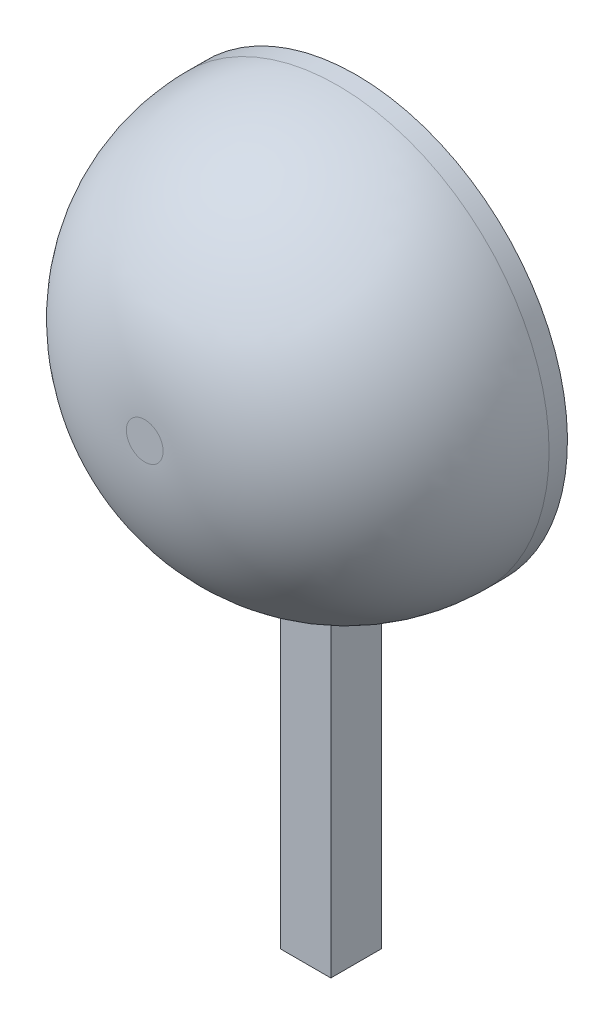
SolidWorks part; units mm, degrees
ref_plane "Front Plane" through (0, 0, 0) normal (0, 0, 1) x (1, 0, 0)
ref_plane "Top Plane" through (0, 0, 0) normal (0, 1, 0) x (1, 0, 0)
ref_plane "Right Plane" through (0, 0, 0) normal (1, 0, 0) x (0, 0, -1)
sketch "Sketch2" plane through (0, 0, 0) normal (0, 0, 1) x (1, 0, 0)
  line L0 (-24.3651, 0) -> (30.0337, 0)
  circle A0 centre (0, 23) radius 23
  dimension "D1" = 46
extrude "Boss-Extrude1" add sketch "Sketch2" along normal blind 23 contours A0
fillet "Fillet1" radius 21 1 edges at (23, 23, 23)
shell "Shell1" thickness 3
fillet "Fillet2" radius 1 1 edges at (20, 23, 0)
ref_plane "Plane1" through (0, 0, 0) normal (0, 1, 0) x (1, 0, 0)
sketch "Sketch5" plane through (0, 0, 0) normal (0, 1, 0) x (1, 0, 0)
  line L0 (-2.75, 0) -> (2.75, 0)
  line L1 (-24.3651, 0) -> (30.0337, 0) construction
  line L2 (-2.75, 0) -> (-2.75, -5.5)
  line L3 (-2.75, -5.5) -> (2.75, -5.5)
  line L4 (2.75, -5.5) -> (2.75, 0)
  point P4 (0, 0)
  dimension "D1" = 5.5
  dimension "D2" = 5.5
extrude "Boss-Extrude3" add sketch "Sketch5" against normal blind 35 and the other way blind 2
